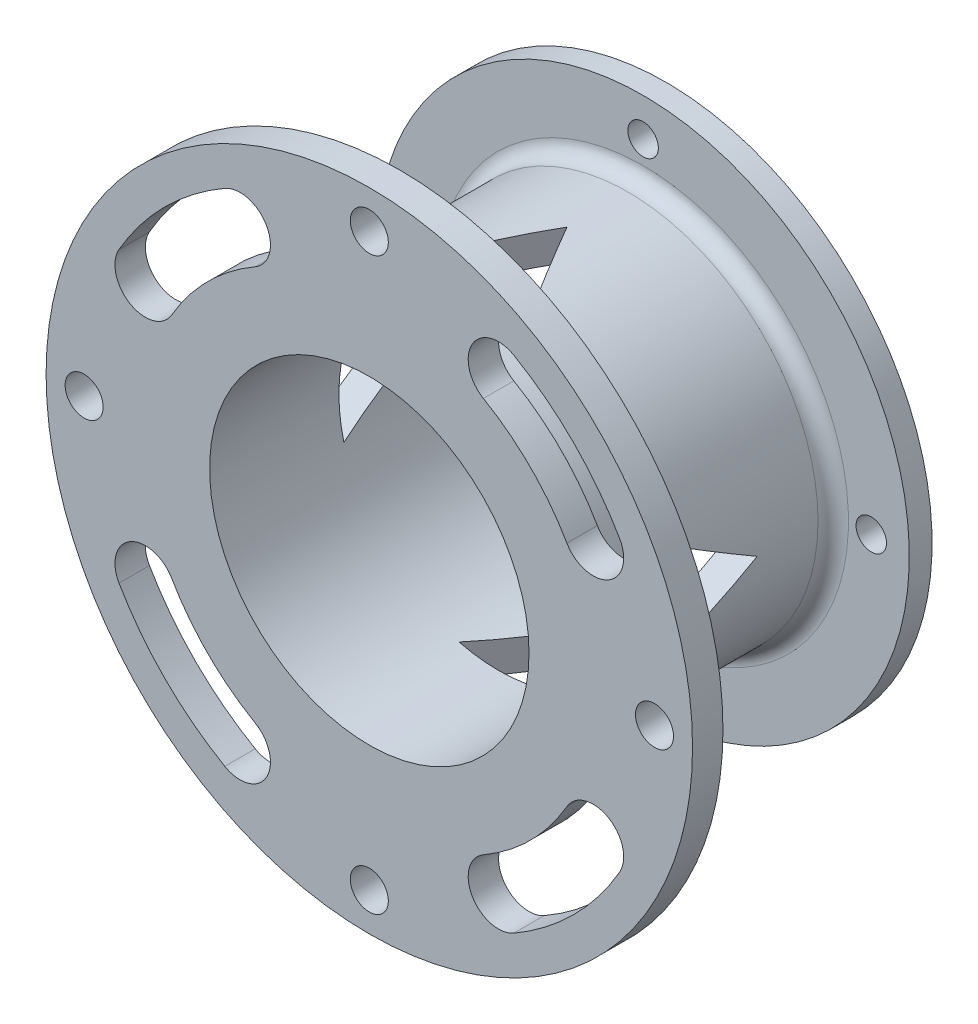
SolidWorks part; units mm, degrees
ref_plane "前视基准面" through (0, 0, 0) normal (0, 0, 1) x (1, 0, 0)
ref_plane "上视基准面" through (0, 0, 0) normal (0, 1, 0) x (1, 0, 0)
ref_plane "右视基准面" through (0, 0, 0) normal (1, 0, 0) x (0, 0, -1)
sketch "草图1" plane through (0, 0, 0) normal (0, 0, 1) x (1, 0, 0)
  circle A0 centre (0, 0) radius 25
  circle A1 centre (0, 0) radius 21
  dimension "D1" = 50
  dimension "D2" = 42
extrude "凸台-拉伸1" add sketch "草图1" along normal blind 39
sketch "草图2" plane through (0, 0, 39) normal (0, 0, 1) x (1, 0, 0)
  circle A0 centre (0, 0) radius 42.5
  circle A1 centre (0, 0) radius 21
  dimension "D1" = 85
extrude "凸台-拉伸2" add sketch "草图2" against normal blind 4
sketch "草图3" plane through (0, 0, 39) normal (0, 0, 1) x (1, 0, 0)
  circle A0 centre (0, 0) radius 37.5 construction
  circle A1 centre (0, 37.5) radius 2.5
  circle A2 centre (37.5, 0) radius 2.5
  circle A3 centre (0, -37.5) radius 2.5
  circle A4 centre (-37.5, 0) radius 2.5
  dimension "D1" = 75
  dimension "D2" = 5
  dimension "D3" = 4
extrude "切除-拉伸1" cut sketch "草图3" against normal blind 4
sketch "草图4" plane through (0, 0, 0) normal (0, 0, -1) x (-1, 0, 0)
  circle A0 centre (0, 0) radius 35
  circle A1 centre (0, 0) radius 21
  dimension "D1" = 70
extrude "凸台-拉伸3" add sketch "草图4" against normal blind 3
sketch "草图5" plane through (0, 0, 0) normal (0, 0, -1) x (-1, 0, 0)
  circle A0 centre (0, 0) radius 30 construction
  circle A1 centre (0, 30) radius 2
  circle A2 centre (30, 0) radius 2
  circle A3 centre (0, -30) radius 2
  circle A4 centre (-30, 0) radius 2
  dimension "D1" = 60
  dimension "D2" = 4
  dimension "D3" = 4
extrude "切除-拉伸2" cut sketch "草图5" against normal blind 3
fillet "圆角1" radius 2 2 edges at (25, 0, 35) (-25, 0, 3)
sketch "草图6" plane through (0, 0, 0) normal (1, 0, 0) x (0, 0, -1)
  line L0 (-5, 25) -> (-33, 25) construction
  line L1 (-13, 0) -> (-22, 5.1962)
  line L2 (-22, 5.1962) -> (-22, -5.1962)
  line L3 (-22, -5.1962) -> (-13, 0)
  circle A0 centre (-19, 0) radius 3 construction
  point P1 (-19, 25)
  point P6 (0, 0)
  point P9 (0, 0)
  dimension "D1" = 6
extrude "切除-拉伸3" cut sketch "草图6" against normal blind 42
pattern_circular "阵列(圆周)1" count 4 over 360 about axis through (0, 0, 0) along (0, 0, 1) of "切除-拉伸3"
sketch "草图7" plane through (0, 0, 39) normal (0, 0, 1) x (1, 0, 0)
  line L0 (-17, 29.4449) -> (0, 0) construction
  line L1 (-29.4449, 17) -> (0, 0) construction
  line L2 (0, 0) -> (0, 20.2643) construction
  arc A0 (-29.4449, 17) -> (-17, 29.4449) centre (0, 0) cw construction
  arc A1 (-19, 32.909) -> (-32.909, 19) centre (0, 0) ccw
  arc A2 (-15, 25.9808) -> (-25.9808, 15) centre (0, 0) ccw
  arc A3 (-15, 25.9808) -> (-19, 32.909) centre (-17, 29.4449) ccw
  arc A4 (-32.909, 19) -> (-25.9808, 15) centre (-29.4449, 17) ccw
  arc A5 (25.9808, 15) -> (15, 25.9808) centre (0, 0) ccw
  arc A6 (25.9808, 15) -> (32.909, 19) centre (29.4449, 17) ccw
  arc A7 (19, 32.909) -> (15, 25.9808) centre (17, 29.4449) ccw
  arc A8 (32.909, 19) -> (19, 32.909) centre (0, 0) ccw
  arc A9 (17, 29.4449) -> (29.4449, 17) centre (0, 0) cw construction
  arc A10 (15, -25.9808) -> (25.9808, -15) centre (0, 0) ccw
  arc A11 (15, -25.9808) -> (19, -32.909) centre (17, -29.4449) ccw
  arc A12 (32.909, -19) -> (25.9808, -15) centre (29.4449, -17) ccw
  arc A13 (19, -32.909) -> (32.909, -19) centre (0, 0) ccw
  arc A14 (29.4449, -17) -> (17, -29.4449) centre (0, 0) cw construction
  arc A15 (-25.9808, -15) -> (-15, -25.9808) centre (0, 0) ccw
  arc A16 (-25.9808, -15) -> (-32.909, -19) centre (-29.4449, -17) ccw
  arc A17 (-19, -32.909) -> (-15, -25.9808) centre (-17, -29.4449) ccw
  arc A18 (-32.909, -19) -> (-19, -32.909) centre (0, 0) ccw
  arc A19 (-17, -29.4449) -> (-29.4449, -17) centre (0, 0) cw construction
  point P3 (-24.0416, 24.0416)
  point P18 (24.0416, 24.0416)
  point P25 (24.0416, -24.0416)
  point P32 (-24.0416, -24.0416)
  dimension "D1" = 30
  dimension "D2" = 38
  dimension "D3" = 30
  dimension "D4" = 30
  dimension "D5" = 4
extrude "切除-拉伸4" cut sketch "草图7" against normal blind 5
